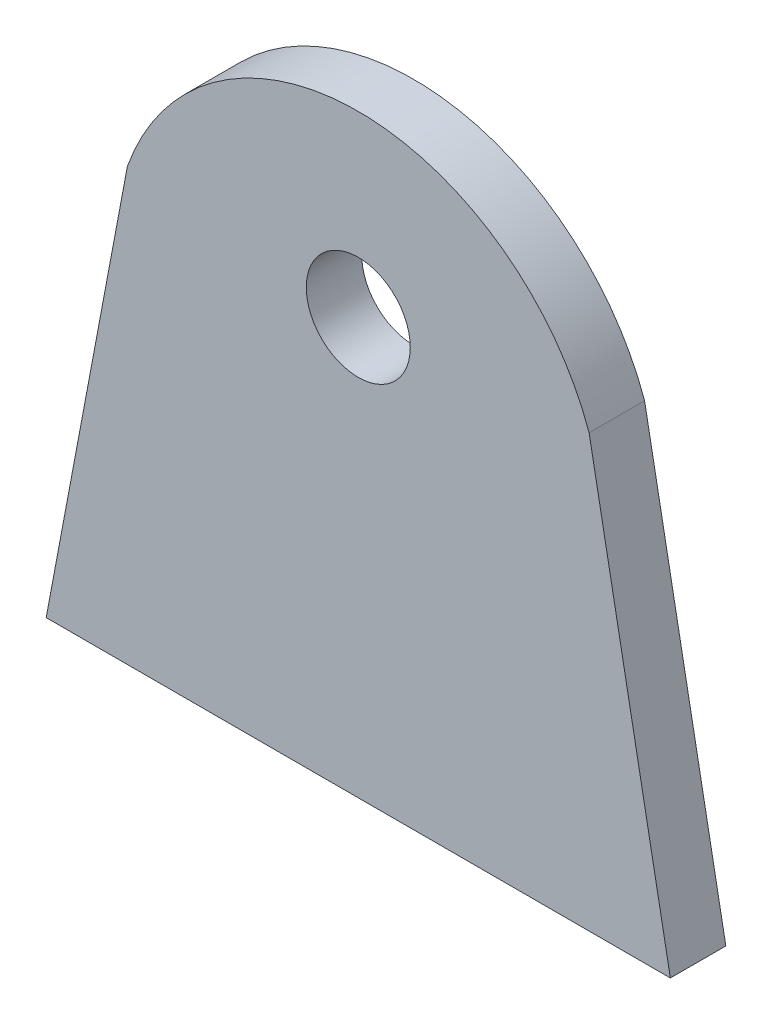
SolidWorks part; units mm, degrees
ref_plane "Front Plane" through (0, 0, 0) normal (0, 0, 1) x (1, 0, 0)
ref_plane "Top Plane" through (0, 0, 0) normal (0, 1, 0) x (1, 0, 0)
ref_plane "Right Plane" through (0, 0, 0) normal (1, 0, 0) x (0, 0, -1)
sketch "Sketch1" plane through (0, 0, 0) normal (0, 0, 1) x (1, 0, 0)
  line L0 (0, 0) -> (28.575, 0)
  line L5 (0, 0) -> (3.7193, 19.7584)
  line L6 (24.8557, 19.7584) -> (28.575, 0)
  circle A0 centre (14.2875, 19.05) radius 2.3813
  arc A1 (3.7193, 19.7584) -> (24.8557, 19.7584) centre (14.2875, 15.9993) cw
  point P5 (14.2875, 0)
  point P8 (0, 0)
  point P10 (14.2875, 27.2161)
  point P13 (14.6887, 28.5294)
  point P14 (30.0661, 20.7555)
  dimension "D3" = 4.7625
  dimension "D1" = 28.575
  dimension "D2" = 8.1661
  dimension "D4" = 19.05
  dimension "D5" = 27.2161
extrude "Boss-Extrude1" add sketch "Sketch1" against normal blind 2.54
